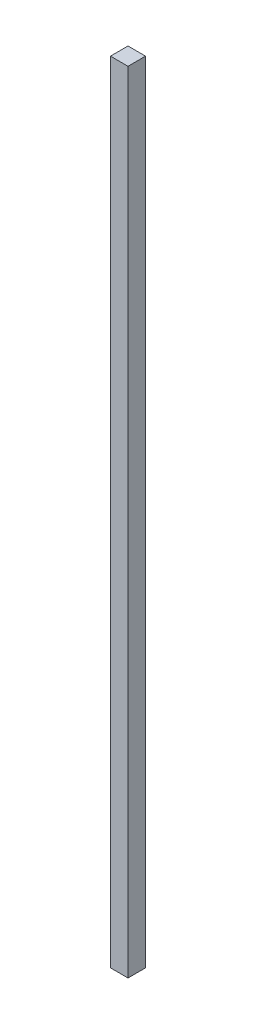
SolidWorks part; units mm, degrees
ref_plane "前视基准面" through (0, 0, 0) normal (0, 0, 1) x (1, 0, 0)
ref_plane "上视基准面" through (0, 0, 0) normal (0, 1, 0) x (1, 0, 0)
ref_plane "右视基准面" through (0, 0, 0) normal (1, 0, 0) x (0, 0, -1)
sketch "Sketch1" plane through (0, 0, 0) normal (0, 1, 0) x (1, 0, 0)
  line L1 (-10, 10) -> (10, 10)
  line L2 (-10, 10) -> (-10, -10)
  line L3 (-10, -10) -> (10, -10)
  line L4 (10, 10) -> (10, -10)
  line L5 (-10, 10) -> (10, -10) construction
  line L6 (-10, -10) -> (10, 10) construction
  point P0 (0, 0)
  dimension "D1" = 20
  dimension "D2" = 20
extrude "Boss-Extrude1" add sketch "Sketch1" along normal blind 900
